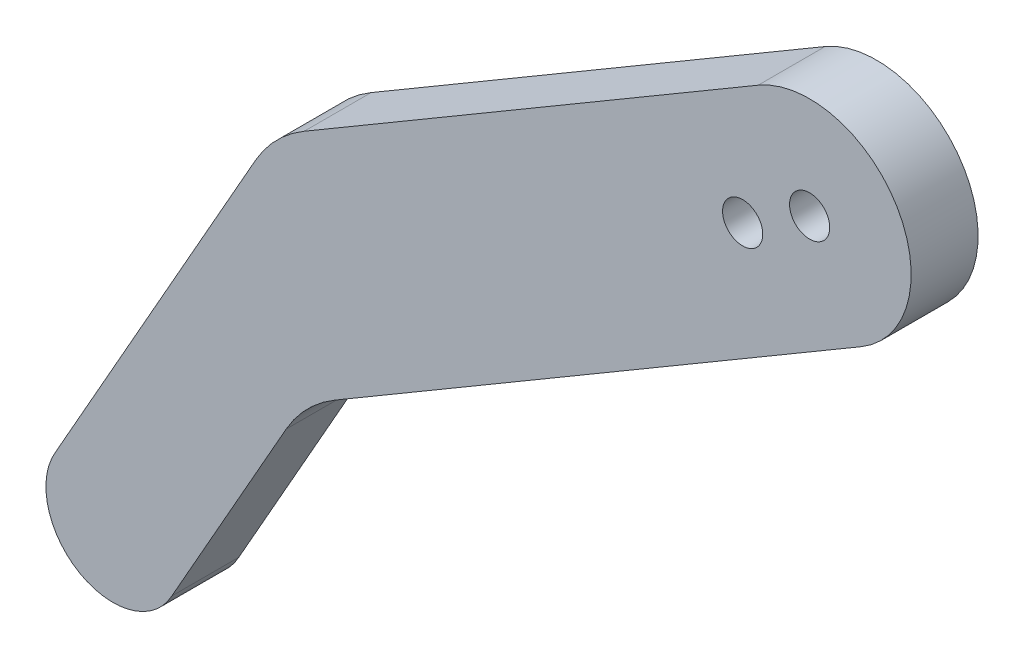
SolidWorks part; units mm, degrees
ref_plane "Front Plane" through (0, 0, 0) normal (0, 0, 1) x (1, 0, 0)
ref_plane "Top Plane" through (0, 0, 0) normal (0, 1, 0) x (1, 0, 0)
ref_plane "Right Plane" through (0, 0, 0) normal (1, 0, 0) x (0, 0, -1)
sketch "Sketch3" plane through (0, 0, 0) normal (0, 0, 1) x (1, 0, 0)
  line L0 (0, 0) -> (14.954, 26.3764)
  line L1 (0, 0) -> (8.6992, -4.932) construction
  line L2 (8.6992, -4.932) -> (17.2416, 10.1355)
  line L3 (18.5854, 30.0652) -> (52.4828, 49.9918)
  line L4 (52.4828, 49.9918) -> (60.1656, 36.9224) construction
  line L5 (20.873, 13.8243) -> (60.1656, 36.9224)
  arc A0 (52.4828, 49.9918) -> (60.1656, 36.9224) centre (56.3242, 43.4571) cw
  arc A1 (0, 0) -> (8.6992, -4.932) centre (4.3053, -2.5441) ccw
  arc A2 (14.954, 26.3764) -> (18.5854, 30.0652) centre (23.6531, 21.4444) cw
  arc A3 (17.2416, 10.1355) -> (20.873, 13.8243) centre (25.9408, 5.2035) cw
  point P10 (16.2755, 28.7073)
  point P13 (19.9017, -5.697)
  point P15 (18.5631, 12.4664)
  dimension "D7" = 5.0008
  dimension "D8" = 10
  dimension "D9" = 10
  dimension "D1" = 33
  dimension "D2" = 42
  dimension "D3" = 150
  dimension "D5" = 20
  dimension "D6" = 10
extrude "Boss-Extrude1" add sketch "Sketch3" along normal blind 5 contours L0 A1 L2 L5 A0 L3
sketch "Sketch4" plane through (0, 0, 5) normal (0, 0, 1) x (1, 0, 0)
  line L0 (52.4828, 49.9918) -> (60.1656, 36.9224) construction
  line L1 (56.3242, 43.4571) -> (21.9477, 23.2489) construction
  line L2 (52.4828, 49.9918) -> (60.1656, 36.9224) construction
  circle A0 centre (56.3242, 43.4571) radius 1.5
  arc A1 (60.1656, 36.9224) -> (52.4828, 49.9918) centre (56.3242, 43.4571) ccw construction
  circle A2 centre (51.3242, 40.5178) radius 1.5
  point P9 (56.3242, 43.4571)
  dimension "D1" = 3
  dimension "D2" = 5
  dimension "D3" = 3
extrude "Cut-Extrude1" cut sketch "Sketch4" against normal blind 7
